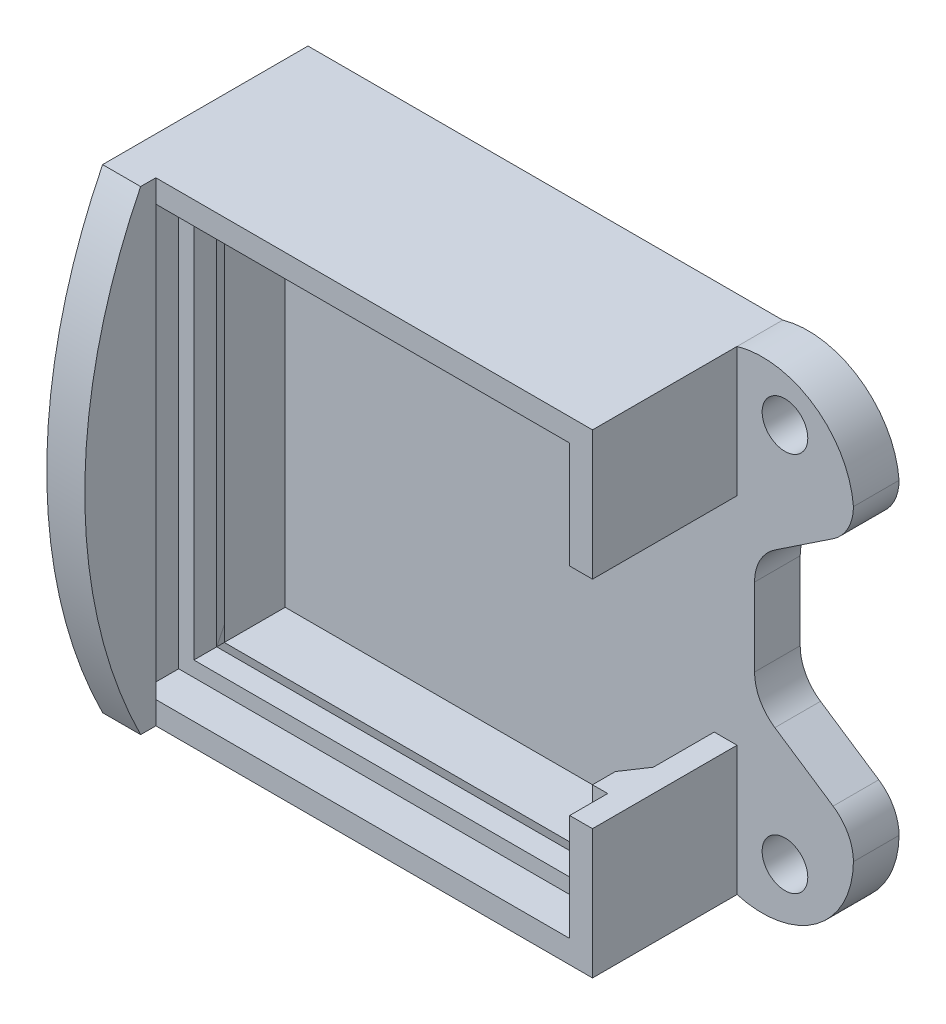
SolidWorks part; units mm, degrees
ref_plane "Alzado" through (0, 0, 0) normal (0, 0, 1) x (1, 0, 0)
ref_plane "Planta" through (0, 0, 0) normal (0, 1, 0) x (1, 0, 0)
ref_plane "Vista lateral" through (0, 0, 0) normal (1, 0, 0) x (0, 0, -1)
sketch "Croquis1" plane through (0, 0, 0) normal (0, 0, 1) x (1, 0, 0)
  line L0 (-52.1973, 0.4619) -> (-52.1973, 4.4619) construction
  line L1 (-2.1973, 16.4619) -> (-44.1973, 16.4619) construction
  line L2 (-52.1973, 4.4619) -> (-50.1973, 4.4619)
  line L3 (-52.1973, -3.5381) -> (-5.1973, -3.5381)
  line L5 (-44.1973, 24.4619) -> (-44.1973, 8.4619)
  line L6 (-44.1973, 8.4619) -> (-50.1973, 4.4619)
  line L7 (-52.1973, 32.4619) -> (-52.1973, 28.4619) construction
  line L8 (-44.1973, 24.4619) -> (-50.1973, 28.4619)
  line L9 (-52.1973, 36.4619) -> (-5.1973, 36.4619)
  line L10 (-52.1973, 28.4619) -> (-50.1973, 28.4619)
  line L11 (-2.1973, -0.5381) -> (-2.1973, 6.3563)
  line L13 (-3.5332, 8.8525) -> (-7.3614, 11.4046)
  line L14 (-8.6973, 13.9008) -> (-8.6973, 19.023)
  line L15 (-3.5332, 24.0713) -> (-7.3614, 21.5191)
  line L16 (-2.1973, 33.4619) -> (-2.1973, 26.5674)
  arc A0 (-52.1973, 36.4619) -> (-52.1973, 28.4619) centre (-52.1973, 32.4619) ccw
  circle A1 centre (-6.6973, 28.9619) radius 1.5
  circle A2 centre (-52.1973, 0.4619) radius 1.5
  circle A3 centre (-6.6973, 3.9619) radius 1.5
  circle A4 centre (-52.1973, 32.4619) radius 1.5
  arc A5 (-5.1973, 36.4619) -> (-2.1973, 33.4619) centre (-5.1973, 33.4619) cw
  arc A6 (-52.1973, -3.5381) -> (-52.1973, 4.4619) centre (-52.1973, 0.4619) cw
  arc A7 (-5.1973, -3.5381) -> (-2.1973, -0.5381) centre (-5.1973, -0.5381) ccw
  arc A8 (-7.3614, 21.5191) -> (-8.6973, 19.023) centre (-5.6973, 19.023) ccw
  arc A9 (-8.6973, 13.9008) -> (-7.3614, 11.4046) centre (-5.6973, 13.9008) ccw
  arc A10 (-3.5332, 24.0713) -> (-2.1973, 26.5674) centre (-5.1973, 26.5674) ccw
  arc A11 (-2.1973, 6.3563) -> (-3.5332, 8.8525) centre (-5.1973, 6.3563) ccw
  point P22 (-2.1973, 36.4619)
  point P26 (-2.1973, -3.5381)
  point P32 (-8.6973, 16.4619)
  point P35 (-8.6973, 20.6286)
  point P41 (-2.1973, 24.9619)
  point P44 (-2.1973, 7.9619)
  dimension "D3" = 50
  dimension "D5" = 20
  dimension "D6" = 4
  dimension "D7" = 42
  dimension "D2" = 3
  dimension "D4" = 3
  dimension "D12" = 3
  dimension "D8" = 7.5
  dimension "D9" = 4.5
  dimension "D10" = 2
  dimension "D11" = 8
  dimension "D13" = 6.5
extrude "Saliente-Extruir1" add sketch "Croquis1" along normal blind 3
sketch "Croquis2" plane through (0, 0, 3) normal (0, 0, 1) x (1, 0, 0)
  line L0 (-52.1973, -3.5381) -> (-5.1973, -3.5381) construction
  line L1 (-39.5473, 30.3619) -> (-11.3473, 30.3619)
  line L2 (-39.5473, 30.3619) -> (-39.5473, 2.1619)
  line L3 (-39.5473, 2.1619) -> (-11.3473, 2.1619)
  line L4 (-11.3473, 30.3619) -> (-11.3473, 2.1619)
  line L6 (-44.1973, 24.4619) -> (-44.1973, 8.4619) construction
  line L8 (-39.5473, 2.1619) -> (-11.3473, 30.3619) construction
  line L10 (-41.0473, 0.6619) -> (-9.8473, 0.6619)
  line L11 (-41.0473, 0.6619) -> (-41.0473, 31.8619)
  line L12 (-41.0473, 31.8619) -> (-9.8473, 31.8619)
  line L13 (-9.8473, 0.6619) -> (-9.8473, 31.8619)
  line L14 (-41.0473, 0.6619) -> (-9.8473, 31.8619) construction
  line L15 (-41.0473, 31.8619) -> (-9.8473, 0.6619) construction
  point P8 (-25.4473, 16.2619)
  dimension "D5" = 1.5
  dimension "D1" = 28.2
  dimension "D2" = 28.2
  dimension "D3" = 5.7
  dimension "D4" = 4.65
  dimension "D6" = 1.5
extrude "Saliente-Extruir2" add sketch "Croquis2" along normal blind 9.5
sketch "Croquis3" plane through (0, 30.3619, 0) normal (0, -1, 0) x (1, 0, 0)
  line L0 (-39.5473, 7) -> (-11.3473, 7) construction
  line L1 (-39.5473, 12.5) -> (-39.5473, 3) construction
  line L2 (-11.3473, 12.5) -> (-11.3473, 3) construction
  line L4 (-11.3473, 3) -> (-39.5473, 3) construction
  dimension "D1" = 4
ref_plane "Plano1" through (0, 0, 7) normal (0, 0, 1) x (1, 0, 0)
sketch "Croquis4" plane through (0, 0, 7) normal (0, 0, 1) x (1, 0, 0)
  line L0 (-11.3473, 30.3619) -> (-39.5473, 2.1619) construction
  line L1 (-39.5473, 30.3619) -> (-11.3473, 30.3619)
  line L2 (-39.5473, 30.3619) -> (-39.5473, 2.1619)
  line L3 (-39.5473, 2.1619) -> (-11.3473, 2.1619)
  line L4 (-11.3473, 30.3619) -> (-11.3473, 2.1619)
  line L6 (-12.3473, 3.1619) -> (-38.5473, 3.1619)
  line L7 (-12.3473, 3.1619) -> (-12.3473, 29.3619)
  line L8 (-12.3473, 29.3619) -> (-38.5473, 29.3619)
  line L9 (-38.5473, 3.1619) -> (-38.5473, 29.3619)
  line L10 (-12.3473, 3.1619) -> (-38.5473, 29.3619) construction
  line L11 (-12.3473, 29.3619) -> (-38.5473, 3.1619) construction
  point P5 (-25.4473, 16.2619)
  dimension "D1" = 28.2
  dimension "D2" = 28.2
  dimension "D3" = 1
extrude "Saliente-Extruir3" add sketch "Croquis4" along normal blind 3
ref_plane "Plano2" through (0, 3.1619, 0) normal (0, -1, 0) x (-1, 0, 0)
sketch "Croquis6" plane through (0, 3.1619, 0) normal (0, -1, 0) x (-1, 0, 0)
  line L0 (38.5473, -8.5) -> (38.5473, -7)
  line L1 (38.5473, -10) -> (38.5473, -7) construction
  line L2 (38.5473, -7) -> (39.5473, -7) construction
  line L3 (39.5473, -7) -> (38.5473, -8.5)
  line L6 (38.5473, -7) -> (39.5473, -7)
sketch "Croquis7" plane through (0, 0, 10) normal (0, 0, 1) x (1, 0, 0)
  line L0 (-38.5473, 29.3619) -> (-39.5473, 30.3619) construction
  line L1 (-12.3473, 29.3619) -> (-11.3473, 30.3619) construction
  line L2 (-38.5473, 3.1619) -> (-39.5473, 2.1619) construction
  line L3 (-39.5473, 30.3619) -> (-39.5473, 2.1619) construction
  line L4 (-12.3473, 3.1619) -> (-11.3473, 2.1619) construction
  line L5 (-39.0473, 29.8619) -> (-11.8473, 29.8619)
  line L6 (-11.8473, 29.8619) -> (-11.8473, 2.6619)
  line L7 (-11.8473, 2.6619) -> (-39.0473, 2.6619)
  line L8 (-39.0473, 2.6619) -> (-39.0473, 29.8619)
sweep "Cortar-Barrer1" cut profiles "Croquis6" path "Croquis7"
sketch "Croquis8" plane through (0, 0, 10) normal (0, 0, 1) x (1, 0, 0)
  line L8 (-11.3473, 30.3619) -> (-39.5473, 30.3619) construction
  line L9 (-30.5473, 30.3619) -> (-23.3473, 30.3619)
  line L10 (-30.5473, 30.3619) -> (-30.5473, 29.3619)
  line L11 (-30.5473, 29.3619) -> (-23.3473, 29.3619)
  line L12 (-23.3473, 30.3619) -> (-23.3473, 29.3619)
  line L13 (-12.3473, 29.3619) -> (-38.5473, 29.3619) construction
  line L14 (-39.5473, 30.3619) -> (-39.5473, 2.1619) construction
  line L15 (-11.3473, 2.1619) -> (-11.3473, 30.3619) construction
  dimension "D1" = 9
  dimension "D2" = 12
extrude "Cortar-Extruir1" cut sketch "Croquis8" against normal up to vertex
sketch "Croquis9" plane through (0, 0, 12.5) normal (0, 0, 1) x (1, 0, 0)
  line L0 (-9.8473, 0.6619) -> (-9.8473, 31.8619) construction
  line L1 (-9.8473, 9.1619) -> (-15.475, 9.1619)
  line L2 (-9.8473, 9.1619) -> (-9.8473, 23.3619)
  line L3 (-9.8473, 23.3619) -> (-15.475, 23.3619)
  line L4 (-15.475, 9.1619) -> (-15.475, 23.3619)
  line L5 (-39.5473, 30.3619) -> (-11.3473, 30.3619) construction
  line L6 (-39.5473, 2.1619) -> (-11.3473, 2.1619) construction
  dimension "D1" = 7
  dimension "D2" = 7
extrude "Cortar-Extruir2" cut sketch "Croquis9" against normal up to vertex
sketch "Croquis10" plane through (0, 0, 12.5) normal (0, 0, 1) x (1, 0, 0)
  line L0 (-9.8473, 31.8619) -> (-41.0473, 31.8619) construction
  line L1 (-41.0473, 0.6619) -> (-38.5473, 0.6619)
  line L2 (-41.0473, 0.6619) -> (-41.0473, 31.8619)
  line L3 (-41.0473, 31.8619) -> (-38.5473, 31.8619)
  line L4 (-38.5473, 0.6619) -> (-38.5473, 31.8619)
  dimension "D1" = 2.5
extrude "Saliente-Extruir4" add sketch "Croquis10" along normal blind 1
sketch "Croquis12" plane through (0, 0, 3) normal (0, 0, 1) x (1, 0, 0)
  line L0 (-9.8473, 31.8619) -> (-41.0473, 31.8619)
  line L1 (-41.0473, 31.8619) -> (-41.0473, 0.6619)
  line L2 (-41.0473, 0.6619) -> (-9.8473, 0.6619)
  line L3 (-2.1973, 26.5674) -> (-2.1973, 40.3991)
  line L4 (-2.1973, 40.3991) -> (-65.3595, 40.3991)
  line L5 (-65.3595, 40.3991) -> (-65.3595, -17.8731)
  line L6 (-65.3595, -17.8731) -> (-2.1973, -17.8731)
  line L7 (-2.1973, -17.8731) -> (-2.1973, 6.3563)
  arc A0 (-9.8473, 31.8619) -> (-2.1973, 26.5674) centre (-8.179, 26.0985) cw
  arc A1 (-9.8473, 0.6619) -> (-2.1973, 6.3563) centre (-8.1969, 6.4304) ccw
  dimension "D1" = 6
  dimension "D2" = 6
extrude "Cortar-Extruir3" cut sketch "Croquis12" against normal up to vertex (3 mm away)
sketch "Croquis13" plane through (-41.0473, 0, 0) normal (-1, 0, 0) x (0, 0, 1)
  line L0 (13.5, 31.8619) -> (13.5, 0.6619)
  arc A0 (13.5, 31.8619) -> (13.5, 0.6619) centre (-17.8311, 16.2619) cw
  dimension "D1" = 35
extrude "Saliente-Extruir5" add sketch "Croquis13" against normal up to vertex
